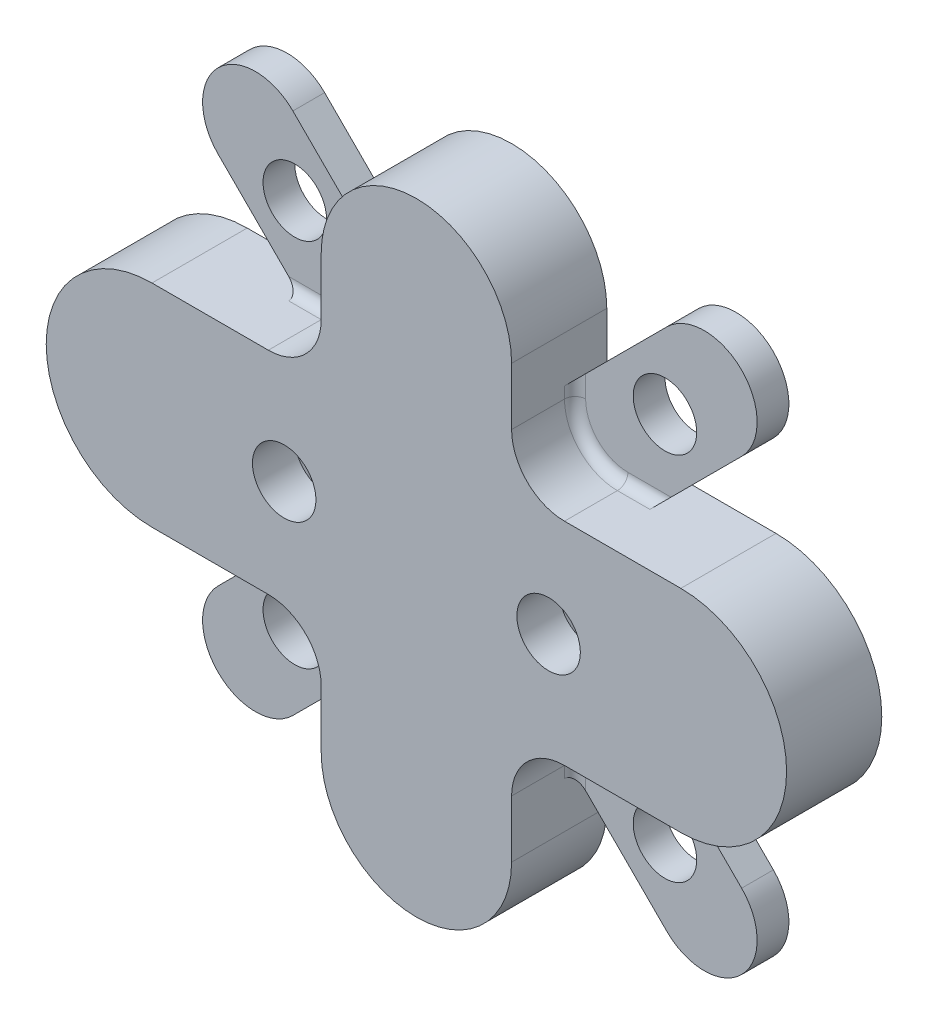
SolidWorks part; units mm, degrees
ref_plane "Спереди" through (0, 0, 0) normal (0, 0, 1) x (1, 0, 0)
ref_plane "Сверху" through (0, 0, 0) normal (0, 1, 0) x (1, 0, 0)
ref_plane "Справа" through (0, 0, 0) normal (1, 0, 0) x (0, 0, -1)
sketch "Sketch1" plane through (0, 0, 0) normal (0, 0, 1) x (1, 0, 0)
  line L0 (0, 0) -> (0, 15.2104)
  line L1 (-24.2091, -24.2091) -> (24.2091, -24.2091) construction
  line L2 (-24.2091, -24.2091) -> (-24.2091, 24.2091) construction
  line L3 (-24.2091, 24.2091) -> (24.2091, 24.2091) construction
  line L4 (24.2091, -24.2091) -> (24.2091, 24.2091) construction
  line L5 (-24.2091, -24.2091) -> (24.2091, 24.2091) construction
  line L6 (-24.2091, 24.2091) -> (24.2091, -24.2091) construction
  line L7 (21.2132, -21.2132) -> (-21.2132, 21.2132) construction
  line L8 (17.6777, -24.7487) -> (-24.7487, 17.6777)
  line L9 (24.7487, -17.6777) -> (-17.6777, 24.7487)
  line L10 (-21.2132, -21.2132) -> (21.2132, 21.2132) construction
  line L11 (-24.7487, -17.6777) -> (17.6777, 24.7487)
  line L12 (-17.6777, -24.7487) -> (24.7487, 17.6777)
  line L13 (-25, 0) -> (25, 0) construction
  line L14 (-25, 10) -> (25, 10)
  line L15 (-25, -10) -> (25, -10)
  circle A0 centre (-17.5, 17.5) radius 3
  circle A1 centre (17.5, 17.5) radius 3
  circle A2 centre (17.5, -17.5) radius 3
  circle A3 centre (-17.5, -17.5) radius 3
  circle A4 centre (12.5, 0) radius 3
  circle A5 centre (-12.5, 0) radius 3
  arc A6 (17.6777, -24.7487) -> (24.7487, -17.6777) centre (21.2132, -21.2132) ccw
  arc A7 (-17.6777, 24.7487) -> (-24.7487, 17.6777) centre (-21.2132, 21.2132) ccw
  arc A8 (-24.7487, -17.6777) -> (-17.6777, -24.7487) centre (-21.2132, -21.2132) ccw
  arc A9 (24.7487, 17.6777) -> (17.6777, 24.7487) centre (21.2132, 21.2132) ccw
  arc A10 (-25, 10) -> (-25, -10) centre (-25, 0) ccw
  arc A11 (25, -10) -> (25, 10) centre (25, 0) ccw
  point P0 (0, 0)
  point P17 (0, 0)
  point P23 (0, 0)
  point P30 (0, 0)
  point P37 (0, 0)
  dimension "D2" = 17.5
  dimension "D4" = 6
  dimension "D5" = 12.5
  dimension "D1" = 17.5
  dimension "D3" = 4
extrude "Boss-Extrude2" add sketch "Sketch1" along normal blind 9
sketch "Sketch5" plane through (0, 0, 9) normal (0, 0, 1) x (1, 0, 0)
  line L0 (0, 20.423) -> (0, -20.423) construction
  line L1 (9, 20.423) -> (9, -20.423)
  line L2 (-9, 20.423) -> (-9, -20.423)
  arc A0 (9, 20.423) -> (-9, 20.423) centre (0, 20.423) ccw
  arc A1 (-9, -20.423) -> (9, -20.423) centre (0, -20.423) ccw
  point P2 (0, 0)
extrude "Boss-Extrude3" add sketch "Sketch5" against normal blind 9
sketch "Sketch4" plane through (0, 0, 9) normal (0, 0, 1) x (1, 0, 0)
  line L0 (0, 0) -> (0, 14.356)
  line L15 (-29.8945, 26.6834) -> (-9, 26.6834)
  line L16 (-29.8945, 26.6834) -> (-29.8945, 10)
  line L17 (-29.8945, 10) -> (-9, 10)
  line L18 (-9, 26.6834) -> (-9, 10)
  line L19 (29.8945, 10) -> (9, 10)
  line L20 (9, 26.6834) -> (9, 10)
  line L21 (29.8945, 26.6834) -> (9, 26.6834)
  line L22 (29.8945, 26.6834) -> (29.8945, 10)
  line L23 (0, 0) -> (22.0433, 0)
  line L24 (29.8945, -26.6834) -> (29.8945, -10)
  line L25 (29.8945, -26.6834) -> (9, -26.6834)
  line L26 (9, -26.6834) -> (9, -10)
  line L27 (29.8945, -10) -> (9, -10)
  line L28 (-29.8945, -10) -> (-9, -10)
  line L29 (-9, -26.6834) -> (-9, -10)
  line L30 (-29.8945, -26.6834) -> (-9, -26.6834)
  line L31 (-29.8945, -26.6834) -> (-29.8945, -10)
  point P0 (0, 0)
  circle M7 centre (17.5, 17.5) radius 3
  line M8 (25, 10) -> (17.0711, 10)
  line M10 (17.0711, 10) -> (24.7487, 17.6777)
  arc M11 (24.7487, 17.6777) -> (17.6777, 24.7487) centre (21.2132, 21.2132) ccw
  line M12 (17.6777, 24.7487) -> (9, 16.0711)
  line M14 (-9, 16.0711) -> (-17.6777, 24.7487)
  arc M15 (-17.6777, 24.7487) -> (-24.7487, 17.6777) centre (-21.2132, 21.2132) ccw
  line M16 (-24.7487, 17.6777) -> (-17.0711, 10)
  line M18 (-17.0711, 10) -> (-25, 10)
  line M20 (-25, -10) -> (-17.0711, -10)
  line M22 (-17.0711, -10) -> (-24.7487, -17.6777)
  arc M23 (-24.7487, -17.6777) -> (-17.6777, -24.7487) centre (-21.2132, -21.2132) ccw
  line M24 (-17.6777, -24.7487) -> (-9, -16.0711)
  line M26 (9, -16.0711) -> (17.6777, -24.7487)
  arc M27 (17.6777, -24.7487) -> (24.7487, -17.6777) centre (21.2132, -21.2132) ccw
  line M28 (24.7487, -17.6777) -> (17.0711, -10)
  line M30 (17.0711, -10) -> (25, -10)
  circle M32 centre (-17.5, 17.5) radius 3
  circle M33 centre (17.5, -17.5) radius 3
  circle M34 centre (-17.5, -17.5) radius 3
  line M45 (-9, 20.423) -> (-9, 16.0711)
  line M46 (-9, -16.0711) -> (-9, -20.423)
  line M48 (9, -20.423) -> (9, -16.0711)
  line M49 (9, 16.0711) -> (9, 20.423)
sketch "Sketch6" plane through (0, 0, 0) normal (0, 0, -1) x (-1, 0, 0)
  line L1 (-6.611, 0) -> (-9.5555, 5.1)
  line L2 (-9.5555, 5.1) -> (-15.4445, 5.1)
  line L3 (-15.4445, 5.1) -> (-18.389, 0)
  line L4 (-18.389, 0) -> (-15.4445, -5.1)
  line L5 (-15.4445, -5.1) -> (-9.5555, -5.1)
  line L6 (-9.5555, -5.1) -> (-6.611, 0)
  line L7 (17.8863, 0.1203) -> (14.9418, 5.2203)
  line L8 (14.9418, 5.2203) -> (9.0529, 5.2203)
  line L9 (9.0529, 5.2203) -> (6.1084, 0.1203)
  line L10 (6.1084, 0.1203) -> (9.0529, -4.9797)
  line L11 (9.0529, -4.9797) -> (14.9418, -4.9797)
  line L12 (14.9418, -4.9797) -> (17.8863, 0.1203)
  circle A2 centre (-12.5, 0) radius 5.1 construction
  circle A3 centre (11.9973, 0.1203) radius 5.1 construction
  dimension "D1" = 10.2
extrude "Cut-Extrude4" cut sketch "Sketch6" against normal blind 5
extrude "Cut-Extrude5" cut sketch "Sketch4" against normal blind 6 contours L18 L15 L16 L17 M18 M16 M15 M14 M45 | L18 L17 M14 M15 M16 M32 | L22 L21 L20 L19 M49 M12 M11 M10 M8 | L20 L19 M12 M10 M11 M7 | L24 L27 L26 L25 M30 M28 M27 M26 M48 | L27 L26 M28 M26 M27 M33 | L29 L28 M24 M22 M23 M34 | L31 L30 L29 L28 M46 M24 M23 M22 M20
fillet "Fillet1" radius 5 4 edges at (9, 10, 6) (-9, 10, 6) (-9, -10, 6) (9, -10, 6)
fillet "Fillet2" radius 1 12 edges at (-9, -15.5355, 3) (-15.5355, -10, 3) (-15.5355, 10, 3) (-9, 15.5355, 3) (9, 15.5355, 3) (15.5355, 10, 3) (15.5355, -10, 3) (9, -15.5355, 3) (-10.4645, -11.4645, 3) (-10.4645, 11.4645, 3) (10.4645, 11.4645, 3) (10.4645, -11.4645, 3)
